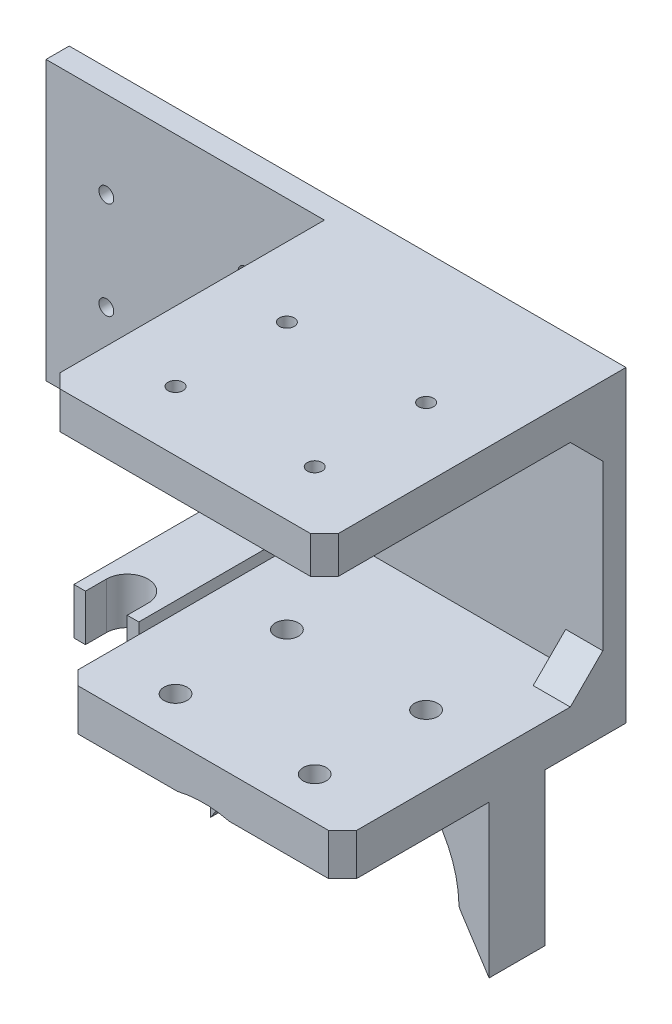
SolidWorks part; units mm, degrees
ref_plane "前视基准面" through (0, 0, 0) normal (0, 0, 1) x (1, 0, 0)
ref_plane "上视基准面" through (0, 0, 0) normal (0, 1, 0) x (1, 0, 0)
ref_plane "右视基准面" through (0, 0, 0) normal (1, 0, 0) x (0, 0, -1)
other "Configuration Table"
sketch "草图1" plane through (0, 0, 0) normal (0, 0, 1) x (1, 0, 0)
  line L0 (-25, 75) -> (-25, 25) construction
  line L2 (35, 20) -> (-85, 20)
  line L3 (35, 20) -> (35, 80)
  line L4 (35, 80) -> (-85, 80)
  line L5 (-85, 20) -> (-85, 80)
  line L6 (35, 20) -> (-85, 80) construction
  line L7 (35, 80) -> (-85, 20) construction
  point P4 (-25, 50)
  dimension "D1" = 60
  dimension "D2" = 120
extrude "凸台-拉伸1" add sketch "草图1" along normal blind 5
sketch "草图2" plane through (0, 0, 0) normal (0, 0, -1) x (-1, 0, 0)
  circle A0 centre (-25, 75) radius 1.75
  circle A1 centre (25, 75) radius 1.75
  circle A2 centre (75, 75) radius 1.75
  circle A3 centre (75, 25) radius 1.75
  circle A4 centre (25, 25) radius 1.75
  circle A5 centre (-25, 25) radius 1.75
  dimension "D1" = 3.5
  dimension "D2" = 3.5
  dimension "D3" = 3.5
  dimension "D4" = 3.5
  dimension "D5" = 3.5
  dimension "D6" = 3.5
sketch "草图3" plane through (0, 0, 5) normal (0, 0, 1) x (1, 0, 0)
  line L0 (-25, 80) -> (-25, 20) construction
  line L1 (35, 80) -> (-85, 80) construction
  line L2 (-85, 20) -> (35, 20) construction
  line L3 (35, 20) -> (35, 80) construction
  line L8 (-25, 80) -> (35, 80)
  line L9 (-25, 80) -> (-25, 72)
  line L10 (-25, 72) -> (35, 72)
  line L11 (35, 80) -> (35, 72)
  point P6 (-25, 50)
  dimension "D1" = 8
extrude "凸台-拉伸3" add sketch "草图3" along normal blind 60
sketch "草图4" plane through (35, 0, 0) normal (1, 0, 0) x (0, 0, -1)
  line L11 (0, -145) -> (0, 145) construction
  line L12 (0, 13.617) -> (-61.0881, 13.617)
  line L13 (0, 13.617) -> (0, 22.617)
  line L14 (0, 22.617) -> (-61.0881, 22.617)
  line L15 (-61.0881, 13.617) -> (-61.0881, 22.617)
  dimension "D1" = 9
extrude "凸台-拉伸4" add sketch "草图4" against normal blind 60
sketch "草图6" plane through (0, 0, 0) normal (0, 0, -1) x (-1, 0, 0)
  line L0 (-5, 13.617) -> (-5, 34.4671) construction
  line L1 (25, 13.617) -> (-35, 13.617) construction
  line L2 (-5, 13.617) -> (-5, -49.7308) construction
  circle A0 centre (-5, -9.2139) radius 23.5
  dimension "D1" = 47
extrude "切除-拉伸1" cut sketch "草图6" against normal through all
sketch "草图7" plane through (0, 0, 0) normal (0, 0, -1) x (-1, 0, 0)
  line L1 (-35, 13.617) -> (25, 13.617)
  line L2 (-35, 13.617) -> (-35, -9.2139)
  line L4 (25, 13.617) -> (25, -9.2139)
  line L5 (-42.9383, -9.2139) -> (32.9383, -9.2139) construction
  line L8 (25, -9.2139) -> (25, -19.2139)
  line L9 (25, -19.2139) -> (18.816, -9.7)
  line L10 (-35, -9.2139) -> (-35, -19.2139)
  line L11 (-35, -19.2139) -> (-28.816, -9.7)
  arc A0 (18.4934, -8.6574) -> (-28.4934, -8.6574) centre (-5, -9.2139) ccw
  arc A1 (18.816, -9.7) -> (18.4934, -8.6574) centre (20.4928, -8.61) cw
  arc A2 (-28.816, -9.7) -> (-28.4934, -8.6574) centre (-30.4928, -8.61) ccw
  point P12 (-5, -9.2139)
  point P17 (18.5, -9.2139)
  point P20 (-28.5, -9.2139)
  line M14 (-35, 13.617) -> (-10.5677, 13.617)
  line M16 (0.5677, 13.617) -> (25, 13.617)
  dimension "D3" = 2
  dimension "D1" = 10
  dimension "D2" = 10
extrude "凸台-拉伸5" add sketch "草图7" against normal blind 50 contours L2 L5 A2 A0 M14 | A1 L5 L4 A0 M16 | L5 A1 L9 L8 | L5 L10 L11 A2
sketch "草图8" plane through (35, 0, 0) normal (1, 0, 0) x (0, 0, -1)
  line L0 (-50, 13.617) -> (-29.5, 13.617)
  line L1 (0, -19.2139) -> (0, 80) construction
  line L2 (-50, -19.2139) -> (0, -19.2139) construction
  line L4 (-29.5, -19.2139) -> (-29.5, 13.617)
  line L5 (-29.5, 13.617) -> (-17.5, 13.617)
  line L6 (-17.5, -19.2139) -> (-17.5, 13.617)
  line L7 (-31, -20.1273) -> (-31, -47.1273) construction
  line L9 (-17.5, -19.2139) -> (0, -19.2139)
  line L10 (0, -19.2139) -> (0, 13.617)
  line L11 (-50, 13.617) -> (-50, -19.2139)
  line L12 (-50, -19.2139) -> (-29.5, -19.2139)
  line L13 (-17.5, 13.617) -> (0, 13.617)
  line M9 (-50, 13.617) -> (-50, -19.2139)
  line M10 (-50, -19.2139) -> (0, -19.2139)
  line M11 (0, -19.2139) -> (0, 80)
  dimension "D1" = 12
  dimension "D2" = 1.5
extrude "切除-拉伸2" cut sketch "草图8" against normal blind 60 contours L4 L0 M10 M9 | L13 L6 M10 M11
sketch "草图9" plane through (0, 20, 0) normal (0, -1, 0) x (1, 0, 0)
  line L0 (-85, 0) -> (-25, 0) construction
  line L3 (-32.5, 0) -> (-41.5, 0)
  line L6 (-41.5, 0) -> (-44, 0)
  line L7 (-41.5, 35.5) -> (-41.5, 40)
  line L8 (-41.5, 40) -> (-44, 40)
  line L9 (-44, 0) -> (-44, 40)
  line L10 (-32.5, 0) -> (-30, 0)
  line L11 (-32.5, 35.5) -> (-32.5, 40)
  line L12 (-32.5, 40) -> (-30, 40)
  line L13 (-30, 0) -> (-30, 40)
  arc A0 (-41.5, 35.5) -> (-32.5, 35.5) centre (-37, 35.5) ccw
  dimension "D1" = 9
  dimension "D2" = 2.5
  dimension "D3" = 40
  dimension "D4" = 2.5
  dimension "D5" = 40
extrude "凸台-拉伸6" add sketch "草图9" along normal blind 10
sketch "草图11" plane through (0, 72, 0) normal (0, -1, 0) x (-1, 0, 0)
  circle A0 centre (-20, -52.0881) radius 1.6
  circle A1 centre (10, -28.0881) radius 1.6
  circle A2 centre (-20, -28.0881) radius 1.6
  circle A3 centre (10, -52.0881) radius 1.6
  point P3 (10, -52.0881)
  point P4 (10, -28.0881)
  point P5 (-20, -28.0881)
extrude "切除-拉伸3" cut sketch "草图11" against normal through all
sketch "草图12" plane through (0, 0, 0) normal (0, 0, -1) x (-1, 0, 0)
  line L0 (42, 67.85) -> (42, 62.85) construction
  line L1 (42, 33.65) -> (42, 38.65) construction
  line L2 (72, 33.65) -> (72, 38.65) construction
  circle A0 centre (42, 40.25) radius 1.6
  circle A1 centre (42, 61.25) radius 1.6
  arc A2 (44.1, 65.75) -> (39.9, 65.75) centre (42, 65.75) ccw construction
  arc A3 (39.9, 35.75) -> (44.1, 35.75) centre (42, 35.75) ccw construction
  circle A4 centre (72, 40.25) radius 1.6
  circle A5 centre (72, 61.25) radius 1.6
  arc A7 (69.9, 35.75) -> (74.1, 35.75) centre (72, 35.75) ccw construction
  dimension "D1" = 3.2
  dimension "D2" = 3.2
  dimension "D3" = 5
  dimension "D5" = 3.2
  dimension "D6" = 3.2
  dimension "D7" = 5
  dimension "D4" = 5
extrude "切除-拉伸4" cut sketch "草图12" against normal through all
sketch "草图13" plane through (35, 0, 0) normal (1, 0, 0) x (0, 0, -1)
  line L0 (-5, 65) -> (-12, 72)
  line L1 (-5, 22.617) -> (-5, 72) construction
  line L2 (-65, 72) -> (-5, 72) construction
  dimension "D1" = 7
  dimension "D2" = 7
rib "筋1" sketch "草图13" sketch "草图13" thickness 8 extrusion direction parallel to sketch draft on no parameters "D1"=8
ref_plane "基准面1" through (5, 0, 0) normal (1, 0, 0) x (0, 0, -1)
mirror "镜向1" about plane through (5, 0, 0) normal (1, 0, 0) of "筋1"
ref_plane "基准面2" through (0, 47.3085, 0) normal (0, -1, 0) x (-1, 0, 0)
mirror "镜向2" about plane through (0, 47.3085, 0) normal (0, -1, 0) of "镜向1", "筋1"
sketch "草图15" plane through (0, 0, 0) normal (0, 0, -1) x (-1, 0, 0)
  line L0 (44, 10) -> (44, 20) construction
  line L1 (25, 13.617) -> (30, 13.617)
  line L2 (25, 13.617) -> (25, 20)
  line L3 (25, 20) -> (30, 20)
  line L4 (30, 13.617) -> (30, 20)
  line L5 (44, 13.617) -> (49, 13.617)
  line L6 (44, 13.617) -> (44, 20)
  line L7 (44, 20) -> (49, 20)
  line L8 (49, 13.617) -> (49, 20)
  line L9 (85, 20) -> (44, 20) construction
  dimension "D1" = 5
extrude "凸台-拉伸7" add sketch "草图15" against normal blind 10
chamfer "倒角2" distance 2 angle 45 1 edges at (-49, 16.8085, 10)
chamfer "倒角3" distance 3 angle 45 4 edges at (35, 18.117, 61.0881) (-25, 18.117, 61.0881) (-25, 76, 65) (35, 76, 65)
sketch "草图16" plane through (0, 22.617, 0) normal (0, 1, 0) x (1, 0, 0)
  circle A0 centre (20, -52.0881) radius 2.5
  circle A1 centre (-10, -52.0881) radius 2.5
  circle A2 centre (-10, -28.0881) radius 2.5
  circle A3 centre (20, -28.0881) radius 2.5
  dimension "D1" = 5
  dimension "D2" = 5
  dimension "D3" = 5
  dimension "D4" = 5
extrude "切除-拉伸5" cut sketch "草图16" against normal through all
sketch "草图18" plane through (0, 0, 0) normal (0, 0, -1) x (-1, 0, 0)
  circle A0 centre (75, 75) radius 3.75
  circle A1 centre (25, 75) radius 3.75
  circle A2 centre (-25, 75) radius 3.75
  circle A3 centre (-25, 25) radius 3.75
  circle A4 centre (25, 25) radius 3.75
  circle A5 centre (75, 25) radius 3.75
  dimension "D1" = 7.5
  dimension "D2" = 7.5
  dimension "D3" = 7.5
  dimension "D4" = 7.5
  dimension "D5" = 7.5
  dimension "D6" = 7.5
extrude "切除-拉伸7" cut sketch "草图18" against normal blind 2
